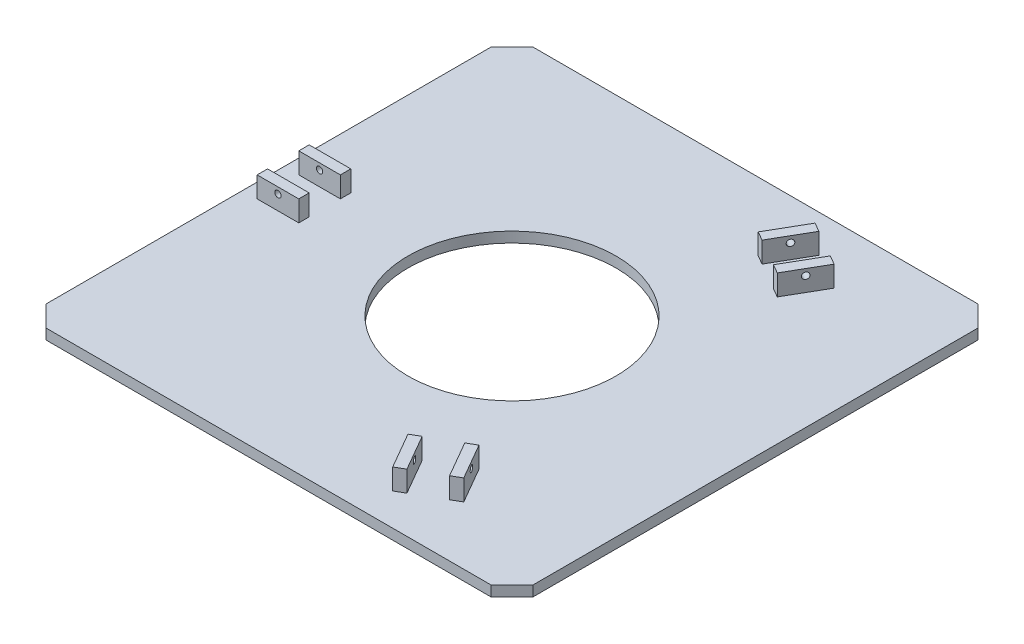
SolidWorks part; units mm, degrees
ref_plane "Front Plane" through (0, 0, 0) normal (0, 0, 1) x (1, 0, 0)
ref_plane "Top Plane" through (0, 0, 0) normal (0, 1, 0) x (1, 0, 0)
ref_plane "Right Plane" through (0, 0, 0) normal (1, 0, 0) x (0, 0, -1)
sketch "Sketch1" plane through (0, 0, 0) normal (0, 1, 0) x (1, 0, 0)
  line L0 (50, 86.6025) -> (50, -86.6025) construction
  line L1 (-117, 117) -> (117, 117) construction
  line L2 (-117, 117) -> (-117, -117) construction
  line L3 (-117, -117) -> (117, -117) construction
  line L4 (117, 117) -> (117, -117) construction
  line L5 (-117, 117) -> (117, -117) construction
  line L6 (-117, -117) -> (117, 117) construction
  line L7 (50, -86.6025) -> (-100, 0) construction
  line L8 (-100, 0) -> (50, 86.6025) construction
  line L9 (44.1747, 101.5128) -> (34.1747, 84.1923)
  line L10 (34.1747, 84.1923) -> (38.5048, 81.6923)
  line L11 (38.5048, 81.6923) -> (48.5048, 99.0128)
  line L12 (48.5048, 99.0128) -> (44.1747, 101.5128)
  line L13 (50, 86.6025) -> (0, 0) construction
  line L14 (0, 0) -> (50, -86.6025) construction
  line L15 (0, 0) -> (-100, 0) construction
  line L16 (50, 86.6025) -> (33.4442, 96.161) construction
  line L17 (61.4952, 91.5128) -> (65.8253, 89.0128)
  line L18 (51.4952, 74.1923) -> (61.4952, 91.5128)
  line L19 (55.8253, 71.6923) -> (51.4952, 74.1923)
  line L20 (65.8253, 89.0128) -> (55.8253, 71.6923)
  line L21 (65.8253, -89.0128) -> (55.8253, -71.6923)
  line L22 (55.8253, -71.6923) -> (51.4952, -74.1923)
  line L23 (51.4952, -74.1923) -> (61.4952, -91.5128)
  line L24 (61.4952, -91.5128) -> (65.8253, -89.0128)
  line L25 (48.5048, -99.0128) -> (44.1747, -101.5128)
  line L26 (38.5048, -81.6923) -> (48.5048, -99.0128)
  line L27 (34.1747, -84.1923) -> (38.5048, -81.6923)
  line L28 (44.1747, -101.5128) -> (34.1747, -84.1923)
  line L29 (-110, -12.5) -> (-90, -12.5)
  line L30 (-90, -12.5) -> (-90, -7.5)
  line L31 (-90, -7.5) -> (-110, -7.5)
  line L32 (-110, -7.5) -> (-110, -12.5)
  line L33 (-110, 7.5) -> (-110, 12.5)
  line L34 (-90, 7.5) -> (-110, 7.5)
  line L35 (-90, 12.5) -> (-90, 7.5)
  line L36 (-110, 12.5) -> (-90, 12.5)
  point P0 (0, 0)
  point P16 (43.5048, 90.3525)
  point P40 (0, 0)
  dimension "D1" = 234
  dimension "D2" = 234
  dimension "D3" = 100
  dimension "D4" = 100
  dimension "D5" = 7.5
  dimension "D6" = 5
  dimension "D7" = 20
  dimension "D8" = 3
extrude "Boss-Extrude1" add sketch "Sketch1" along normal blind 10
sketch "Sketch2" plane through (0, 0, 0) normal (0, 1, 0) x (1, 0, 0)
  line L0 (-117, 107) -> (-107, 117)
  line L1 (-107, 117) -> (107, 117)
  line L2 (-117, 107) -> (-117, -107)
  line L3 (-107, -117) -> (107, -117)
  line L4 (117, 107) -> (117, -107)
  line L5 (-117, 117) -> (117, -117) construction
  line L6 (-117, -117) -> (117, 117) construction
  line L7 (107, 117) -> (117, 107)
  line L8 (-117, -107) -> (-107, -117)
  line L9 (107, -117) -> (117, -107)
  circle A0 centre (0, 0) radius 50
  point P0 (0, 0)
  dimension "D3" = 100
  dimension "D1" = 234
  dimension "D2" = 234
extrude "Boss-Extrude2" add sketch "Sketch2" against normal blind 5
sketch "Sketch3" plane through (0, 0, 12.5) normal (0, 0, 1) x (1, 0, 0)
  line L0 (-110, 0) -> (-90, 0) construction
  line L1 (-110, 10) -> (-110, 0) construction
  circle A0 centre (-100, 7) radius 1.525
  point P4 (0, 0)
  dimension "D2" = 3.05
  dimension "D1" = 7
  dimension "D3" = 10
extrude "Cut-Extrude1" cut sketch "Sketch3" against normal blind 30
sketch "Sketch4" plane through (10.8253, 0, -6.25) normal (0.866, 0, -0.5) x (-0.5, 0, -0.866)
  line L0 (-110, 10) -> (-110, 0) construction
  line L1 (-151.1647, 0) -> (34.1647, 0) construction
  circle A0 centre (-100, 7) radius 1.525
  dimension "D3" = 3.05
  dimension "D1" = 10
  dimension "D2" = 7
extrude "Cut-Extrude2" cut sketch "Sketch4" against normal blind 30
sketch "Sketch5" plane through (-10.8253, 0, -6.25) normal (-0.866, 0, -0.5) x (-0.5, 0, 0.866)
  line L0 (-110, 10) -> (-110, 0) construction
  line L1 (-154.825, 0) -> (-47.825, 0) construction
  circle A0 centre (-100, 7) radius 1.525
  dimension "D3" = 3.05
  dimension "D1" = 10
  dimension "D2" = 7
extrude "Cut-Extrude3" cut sketch "Sketch5" against normal blind 30
